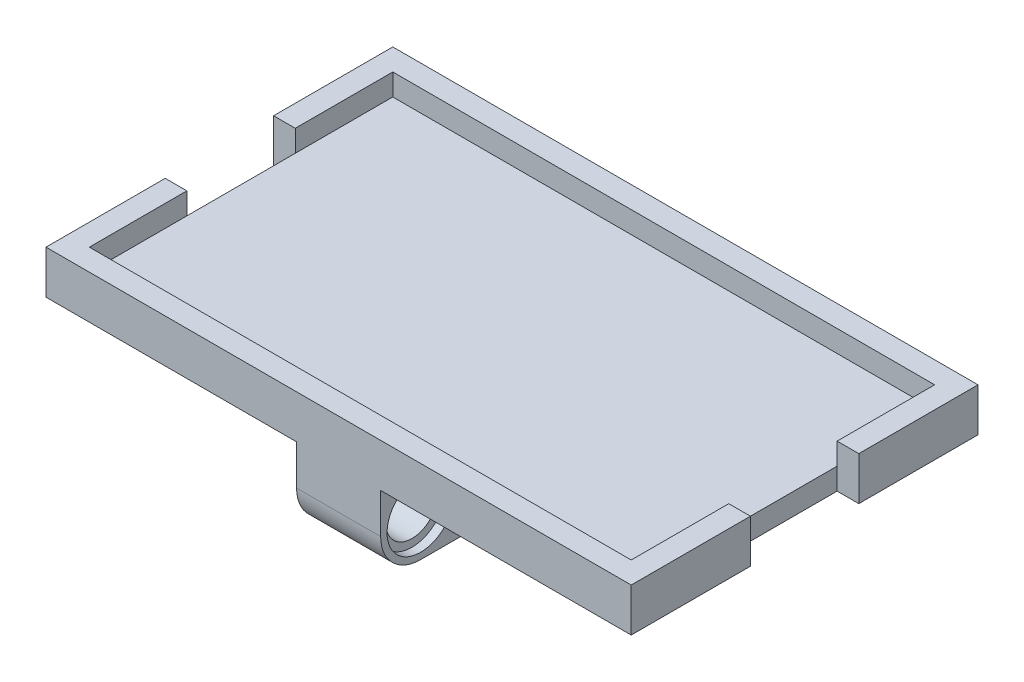
SolidWorks part; units mm, degrees
ref_plane "Front Plane" through (0, 0, 0) normal (0, 0, 1) x (1, 0, 0)
ref_plane "Top Plane" through (0, 0, 0) normal (0, 1, 0) x (1, 0, 0)
ref_plane "Right Plane" through (0, 0, 0) normal (1, 0, 0) x (0, 0, -1)
sketch "Sketch1" plane through (0, 0, 0) normal (0, 1, 0) x (1, 0, 0)
  line L1 (0, 0) -> (54, 0)
  line L2 (0, 0) -> (0, 32)
  line L3 (0, 32) -> (54, 32)
  line L4 (54, 0) -> (54, 32)
  dimension "D1" = 54
  dimension "D2" = 32
extrude "Boss-Extrude1" add sketch "Sketch1" along normal blind 2
sketch "Sketch2" plane through (0, 2, 0) normal (0, 1, 0) x (1, 0, 0)
  line L1 (0, 32) -> (50.6302, 32)
  line L2 (0, 32) -> (0, 29.0449)
  line L5 (50.6302, 32.2515) -> (54, 32.2515)
  line L7 (50.6302, 0) -> (54, 0)
  line L8 (54, 32.2515) -> (54, 0)
  line L14 (0, 0) -> (54, 0)
  line L15 (0, 0) -> (0, 32)
  line L16 (0, 32) -> (54, 32)
  line L17 (2, 30) -> (2, 2)
  line L18 (2, 2) -> (52, 2)
  line L19 (52, 2) -> (52, 30)
  line L20 (52, 30) -> (2, 30)
  line L21 (2, 30) -> (2, 2)
  line L22 (2, 2) -> (52, 2)
  line L23 (52, 2) -> (52, 30)
  line L24 (52, 30) -> (2, 30)
  line L25 (54, 0) -> (54, 32)
  line M5 (0, 32) -> (0, 0)
  line M6 (0, 0) -> (54, 0)
  line M7 (54, 0) -> (54, 32)
  line M8 (54, 32) -> (0, 32)
  dimension "D1" = 2
extrude "Boss-Extrude2" add sketch "Sketch2" along normal blind 2 contours L24 L23 L22 L21 M8 M5 M6 M7
sketch "Sketch3" plane through (0, 4, 0) normal (0, 1, 0) x (1, 0, 0)
  line L0 (0, 32) -> (0, 0) construction
  line L1 (0, 21) -> (2, 21)
  line L2 (0, 21) -> (0, 11)
  line L3 (0, 11) -> (2, 11)
  line L4 (2, 21) -> (2, 11)
  line L5 (2, 30) -> (2, 2) construction
  line L6 (54, 0) -> (54, 32) construction
  line L7 (54, 21) -> (52, 21)
  line L8 (54, 21) -> (54, 11)
  line L9 (54, 11) -> (52, 11)
  line L10 (52, 21) -> (52, 11)
  line L11 (52, 2) -> (52, 30) construction
  line L12 (54, 32) -> (0, 32) construction
  dimension "D1" = 11
  dimension "D2" = 11
  dimension "D3" = 10
  dimension "D4" = 10
extrude "Cut-Extrude1" cut sketch "Sketch3" against normal blind 4
sketch "Sketch4" plane through (0, 0, 0) normal (0, -1, 0) x (1, 0, 0)
  line L0 (0, 0) -> (54, 0) construction
  line L1 (23.12, 0) -> (30.88, 0)
  line L2 (23.12, 0) -> (23.12, -23.32)
  line L3 (23.12, -23.32) -> (30.88, -23.32)
  line L4 (30.88, 0) -> (30.88, -23.32)
  line L5 (54, 0) -> (54, -11) construction
  dimension "D1" = 0
  dimension "D2" = 23.32
  dimension "D3" = 7.76
  dimension "D4" = 23.12
extrude "Boss-Extrude3" add sketch "Sketch4" along normal blind 7.38
sketch "Sketch5" plane through (30.88, 0, 0) normal (1, 0, 0) x (0, 0, -1)
  line L0 (23.32, -7.38) -> (23.32, 0) construction
  line L1 (23.32, -7.38) -> (0, -7.38) construction
  circle A0 centre (3.69, -3.69) radius 2.4
  circle A1 centre (11.66, -3.69) radius 2.4
  circle A2 centre (19.63, -3.69) radius 2.4
  dimension "D4" = 4.8
  dimension "D5" = 4.8
  dimension "D9" = 4.8
  dimension "D1" = 3.69
  dimension "D2" = 3.69
  dimension "D3" = 7.97
  dimension "D6" = 3.69
  dimension "D7" = 7.97
  dimension "D8" = 3.69
extrude "Cut-Extrude2" cut sketch "Sketch5" against normal blind 7.79
sketch "Sketch6" plane through (23.12, 0, 0) normal (-1, 0, 0) x (0, 0, 1)
  circle A0 centre (-11.66, -3.69) radius 3.1
  circle A1 centre (-3.69, -3.69) radius 3.1
  circle A2 centre (-19.63, -3.69) radius 3.1
  dimension "D1" = 6.2
  dimension "D2" = 6.2
  dimension "D3" = 6.2
extrude "Cut-Extrude3" cut sketch "Sketch6" against normal blind 0.8
sketch "Sketch7" plane through (30.88, 0, 0) normal (1, 0, 0) x (0, 0, -1)
  circle A0 centre (3.69, -3.69) radius 3.1
  circle A1 centre (11.66, -3.69) radius 3.1
  circle A2 centre (19.63, -3.69) radius 3.1
  dimension "D1" = 6.2
  dimension "D2" = 6.2
  dimension "D3" = 6.2
extrude "Cut-Extrude4" cut sketch "Sketch7" against normal blind 0.8
fillet "Fillet1" radius 3.69 2 edges at (27, -7.38, 0) (27, -7.38, -23.32)
